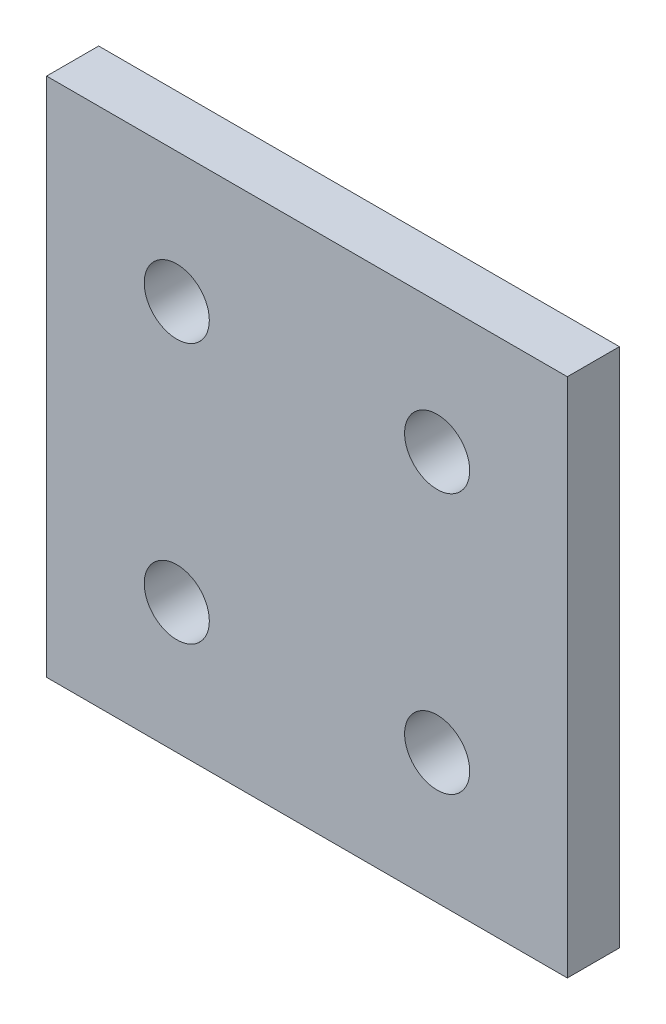
SolidWorks part; units mm, degrees
ref_plane "Front" through (0, 0, 0) normal (0, 0, 1) x (1, 0, 0)
ref_plane "Top" through (0, 0, 0) normal (0, 1, 0) x (1, 0, 0)
ref_plane "Right" through (0, 0, 0) normal (1, 0, 0) x (0, 0, -1)
sketch "Sketch1" plane through (0, 0, 0) normal (0, 0, 1) x (1, 0, 0)
  line L1 (-20, -20) -> (20, -20)
  line L2 (-20, -20) -> (-20, 20)
  line L3 (-20, 20) -> (20, 20)
  line L4 (20, -20) -> (20, 20)
  line L5 (-20, -20) -> (20, 20) construction
  line L6 (-20, 20) -> (20, -20) construction
  circle A0 centre (-10, 10) radius 2.5
  circle A1 centre (10, 10) radius 2.5
  circle A2 centre (10, -10) radius 2.5
  circle A3 centre (-10, -10) radius 2.5
  point P0 (0, 0)
  point P11 (0, 0)
  point P14 (0, 0)
  point P17 (0, 0)
  dimension "D4" = 5
  dimension "D1" = 40
  dimension "D2" = 40
  dimension "D3" = 10
  dimension "D5" = 4
extrude "Boss-Extrude1" add sketch "Sketch1" along normal blind 4
